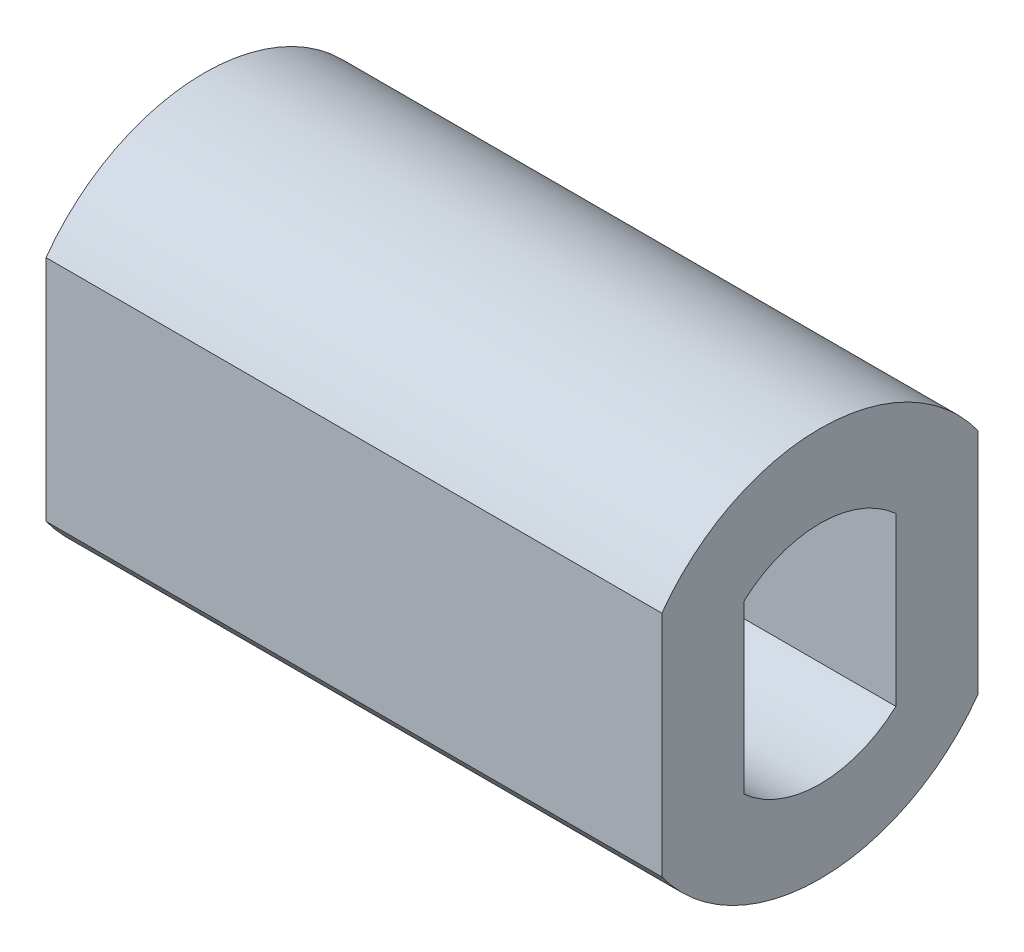
SolidWorks part; units mm, degrees
ref_plane "Front Plane" through (0, 0, 0) normal (0, 0, 1) x (1, 0, 0)
ref_plane "Top Plane" through (0, 0, 0) normal (0, 1, 0) x (1, 0, 0)
ref_plane "Right Plane" through (0, 0, 0) normal (1, 0, 0) x (0, 0, -1)
sketch "Sketch1" plane through (0, 0, 0) normal (1, 0, 0) x (0, 0, -1)
  circle A0 centre (0, 0) radius 2.75
  dimension "D1" = 5.5
extrude "Boss-Extrude1" add sketch "Sketch1" along normal mid plane 22
sketch "Sketch2" plane through (11, 0, 0) normal (1, 0, 0) x (0, 0, -1)
  line L0 (-1.85, 2.0347) -> (-1.85, -2.0347)
  line L1 (1.85, 2.0347) -> (1.85, -2.0347)
  arc A0 (-1.85, 2.0347) -> (-1.85, -2.0347) centre (0, 0) ccw
  arc A1 (1.85, -2.0347) -> (1.85, 2.0347) centre (0, 0) ccw
  dimension "D3" = 5.5
  dimension "D1" = 3.7
  dimension "D2" = 1.85
extrude "Cut-Extrude1" cut sketch "Sketch2" against normal through all
sketch "Sketch3" plane through (11, 0, 0) normal (1, 0, 0) x (0, 0, -1)
  line L0 (-3.85, 2.7821) -> (-3.85, -2.7821)
  line L1 (3.85, -2.7821) -> (3.85, 2.7821)
  line L2 (-1.85, 2.0347) -> (-1.85, -2.0347)
  line L3 (1.85, -2.0347) -> (1.85, 2.0347)
  line L4 (-1.85, 2.0347) -> (-1.85, -2.0347)
  line L5 (1.85, -2.0347) -> (1.85, 2.0347)
  arc A0 (-3.85, -2.7821) -> (3.85, -2.7821) centre (0, 0) ccw
  arc A1 (3.85, 2.7821) -> (-3.85, 2.7821) centre (0, 0) ccw
  arc A2 (-1.85, -2.0347) -> (1.85, -2.0347) centre (0, 0) ccw
  arc A3 (1.85, 2.0347) -> (-1.85, 2.0347) centre (0, 0) ccw
  arc A4 (-1.85, -2.0347) -> (1.85, -2.0347) centre (0, 0) ccw
  arc A5 (1.85, 2.0347) -> (-1.85, 2.0347) centre (0, 0) ccw
  dimension "D1" = 0
  dimension "D2" = 2
extrude "Boss-Extrude2" add sketch "Sketch3" along normal blind 10 from offset 1 offset against normal yes
sketch "Sketch5" plane through (-3, 0, 0) normal (-1, 0, 0) x (0, 0, 1)
  line L2 (1.85, -2.0347) -> (1.85, 2.0347)
  line L3 (-1.85, 2.0347) -> (-1.85, -2.0347)
  line L4 (1.85, -2.0347) -> (1.85, 2.0347)
  line L5 (-1.85, 2.0347) -> (-1.85, -2.0347)
  arc A3 (-1.85, -2.0347) -> (1.85, -2.0347) centre (0, 0) ccw
  arc A4 (1.85, 2.0347) -> (-1.85, 2.0347) centre (0, 0) ccw
  arc A5 (-1.85, -2.0347) -> (1.85, -2.0347) centre (0, 0) ccw
  arc A6 (1.85, 2.0347) -> (-1.85, 2.0347) centre (0, 0) ccw
  dimension "D1" = 0
extrude "Cut-Extrude2" cut sketch "Sketch5" along normal up to surface (21 mm away) from surface
sketch "Sketch6" plane through (10, 0, 0) normal (-1, 0, 0) x (0, 0, 1)
  line L0 (-1.4, 2.8775) -> (-1.4, -2.8775)
  line L3 (-3.85, 2.7821) -> (-3.85, -2.7821)
  line L4 (3.85, -2.7821) -> (3.85, 2.7821)
  line L5 (-3.85, 2.7821) -> (-3.85, -2.7821)
  line L6 (3.85, -2.7821) -> (3.85, 2.7821)
  circle A0 centre (0, 0) radius 3.2
  arc A3 (3.85, 2.7821) -> (-3.85, 2.7821) centre (0, 0) ccw
  arc A4 (-3.85, -2.7821) -> (3.85, -2.7821) centre (0, 0) ccw
  arc A5 (3.85, 2.7821) -> (-3.85, 2.7821) centre (0, 0) ccw
  arc A6 (-3.85, -2.7821) -> (3.85, -2.7821) centre (0, 0) ccw
  point P5 (3.2, 0)
  arc M7 (3.85, 2.7821) -> (-3.85, 2.7821) centre (0, 0) ccw
  line M8 (-3.85, 2.7821) -> (-3.85, -2.7821)
  arc M9 (-3.85, -2.7821) -> (3.85, -2.7821) centre (0, 0) ccw
  line M10 (3.85, -2.7821) -> (3.85, 2.7821)
  dimension "D1" = 6.4
  dimension "D2" = 4.6
  dimension "D3" = 0
extrude "Boss-Extrude3" add sketch "Sketch6" along normal blind 5 contours A0 M10 M7 M8 M9 | L0 A0
